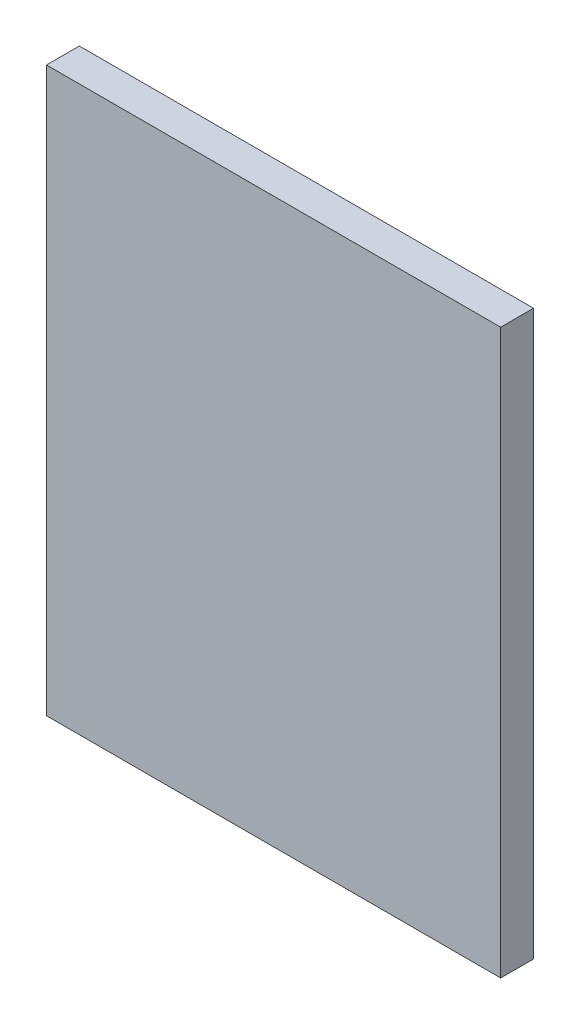
SolidWorks part; units mm, degrees
material "Pine"
ref_plane "Front Plane" through (0, 0, 0) normal (0, 0, 1) x (1, 0, 0)
ref_plane "Top Plane" through (0, 0, 0) normal (0, 1, 0) x (1, 0, 0)
ref_plane "Right Plane" through (0, 0, 0) normal (1, 0, 0) x (0, 0, -1)
sketch "Sketch3" plane through (0, 0, 0) normal (0, 0, 1) x (1, 0, 0)
  line L4 (417, 206) -> (583, 206)
  line L5 (417, 206) -> (417, 0)
  line L6 (417, 0) -> (583, 0)
  line L7 (583, 206) -> (583, 0)
  line L8 (417, 206) -> (583, 0) construction
  line L9 (417, 0) -> (583, 206) construction
  point P6 (500, 103)
  dimension "D1" = 166
  dimension "D2" = 206
extrude "Boss-Extrude2" add sketch "Sketch3" along normal blind 12 separate body
sketch "Sketch4" [suppressed] plane through (0, 0, 12) normal (0, 0, 1) x (1, 0, 0)
  line L1 (442.6085, 191.5854) -> (556.8131, 191.5854)
  line L2 (432.6085, 181.5854) -> (432.6085, 99.4004)
  line L3 (442.6085, 89.4004) -> (556.8131, 89.4004)
  line L4 (566.8131, 181.5854) -> (566.8131, 99.4004)
  line L5 (432.6085, 191.5854) -> (566.8131, 89.4004) construction
  line L6 (432.6085, 89.4004) -> (566.8131, 191.5854) construction
  line L7 (438.5839, 77.616) -> (560.5839, 77.616) construction
  line L8 (438.5839, 77.616) -> (438.5839, -46.384) construction
  line L9 (438.5839, -46.384) -> (560.5839, -46.384) construction
  line L10 (560.5839, 77.616) -> (560.5839, -46.384) construction
  line L11 (213.067, 66.7937) -> (345.067, 66.7937) construction
  line L12 (213.067, 66.7937) -> (213.067, -0.2063) construction
  line L13 (213.067, -0.2063) -> (345.067, -0.2063) construction
  line L14 (345.067, 66.7937) -> (345.067, -0.2063) construction
  line L15 (465.4441, 183.8582) -> (567.4441, 183.8582)
  line L16 (465.4441, 183.8582) -> (465.4441, 98.8582)
  line L17 (465.4441, 98.8582) -> (567.4441, 98.8582)
  line L18 (567.4441, 183.8582) -> (567.4441, 98.8582)
  arc A0 (432.6085, 99.4004) -> (442.6085, 89.4004) centre (442.6085, 99.4004) ccw
  arc A1 (556.8131, 89.4004) -> (566.8131, 99.4004) centre (556.8131, 99.4004) ccw
  arc A2 (556.8131, 191.5854) -> (566.8131, 181.5854) centre (556.8131, 181.5854) cw
  arc A3 (442.6085, 191.5854) -> (432.6085, 181.5854) centre (442.6085, 181.5854) ccw
  point P0 (499.7108, 140.4929)
  dimension "D1" = 10
equation "\"LENGTH\" = 1000mm"
equation "\"PLY\"= 12mm"
equation "\"CENTER_BRACE_LENGTH\" = 393mm"
equation "\"PANEL_WIDTH\"= \"LENGTH\" - \"CENTER_BRACE_LENGTH\" * 2 - \"PLY\" * 4"
equation "\"D1@Boss-Extrude2\"=\"PLY\""
equation "\"D1@Sketch3\"=\"PANEL_WIDTH\""
equation "\"PANEL_SMALL_HEIGHT\" = 70mm"
equation "\"D2@Sketch3\"=\"WIDTH\" - \"PLY\" * 2 - \"PANEL_SMALL_HEIGHT\""
equation "\"WIDTH\" = 300mm"
